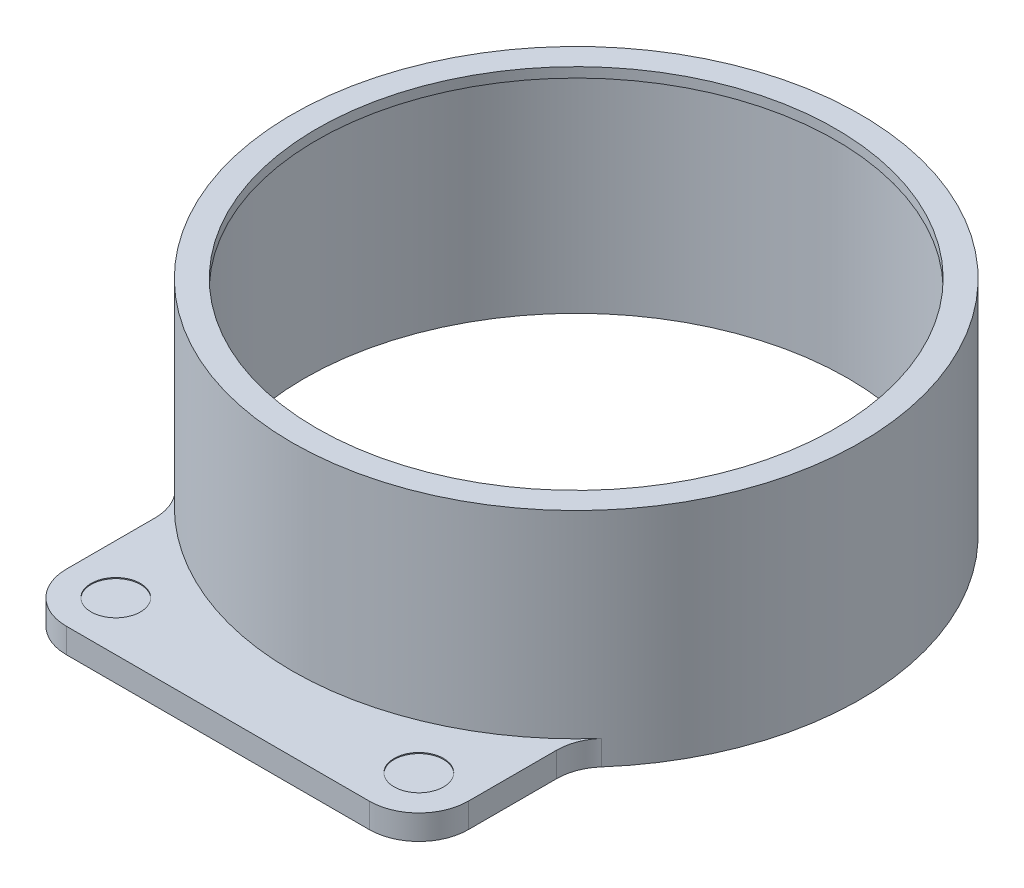
SolidWorks part; units mm, degrees
ref_plane "Front Plane" through (0, 0, 0) normal (0, 0, 1) x (1, 0, 0)
ref_plane "Top Plane" through (0, 0, 0) normal (0, 1, 0) x (1, 0, 0)
ref_plane "Right Plane" through (0, 0, 0) normal (1, 0, 0) x (0, 0, -1)
sketch "Sketch1" plane through (0, 0, 0) normal (0, 1, 0) x (1, 0, 0)
  circle A0 centre (0, 0) radius 69.8659
  circle A1 centre (0, 0) radius 66.675
  dimension "D1" = 133.35
  dimension "D2" = 139.7317
extrude "Boss-Extrude1" add sketch "Sketch1" along normal blind 2.54
sketch "Sketch2" plane through (0, 2.54, 0) normal (0, 1, 0) x (1, 0, 0)
  circle A0 centre (0, 0) radius 73.025
  circle A1 centre (0, 0) radius 69.8659 construction
  circle A2 centre (0, 0) radius 69.8659
  dimension "D1" = 146.05
extrude "Boss-Extrude2" add sketch "Sketch2" against normal blind 57.15
sketch "Sketch3" plane through (0, -54.61, 0) normal (0, -1, 0) x (1, 0, 0)
  line L0 (0, 73.025) -> (0, 66.675) construction
  line L1 (-51.6365, 51.6365) -> (-51.6365, 92.075)
  line L2 (-51.6365, 92.075) -> (51.6365, 92.075)
  line L3 (0, 73.025) -> (0, 92.075) construction
  line L4 (0, 66.675) -> (0, 0) construction
  line L5 (0, 0) -> (-51.6365, 51.6365) construction
  line L6 (51.6365, 51.6365) -> (51.6365, 92.075)
  circle A0 centre (0, 0) radius 73.025 construction
  circle A1 centre (0, 0) radius 66.675 construction
  arc A2 (51.6365, 51.6365) -> (-51.6365, 51.6365) centre (0, 0) ccw
  dimension "D1" = 45
  dimension "D2" = 19.05
extrude "Boss-Extrude3" add sketch "Sketch3" against normal blind 6.35
fillet "Fillet2" radius 12.7 4 edges at (51.6365, -51.435, 92.075) (51.6365, -51.435, 51.6365) (-51.6365, -51.435, 92.075) (-51.6365, -51.435, 51.6365)
sketch "Sketch4" plane through (0, -48.26, 0) normal (0, 1, 0) x (1, 0, 0)
  circle A0 centre (-38.9365, -79.375) radius 6.35
  circle A1 centre (38.9365, -79.375) radius 6.35
  dimension "D1" = 12.7
extrude "Cut-Extrude1" cut sketch "Sketch4" against normal blind 0.254
